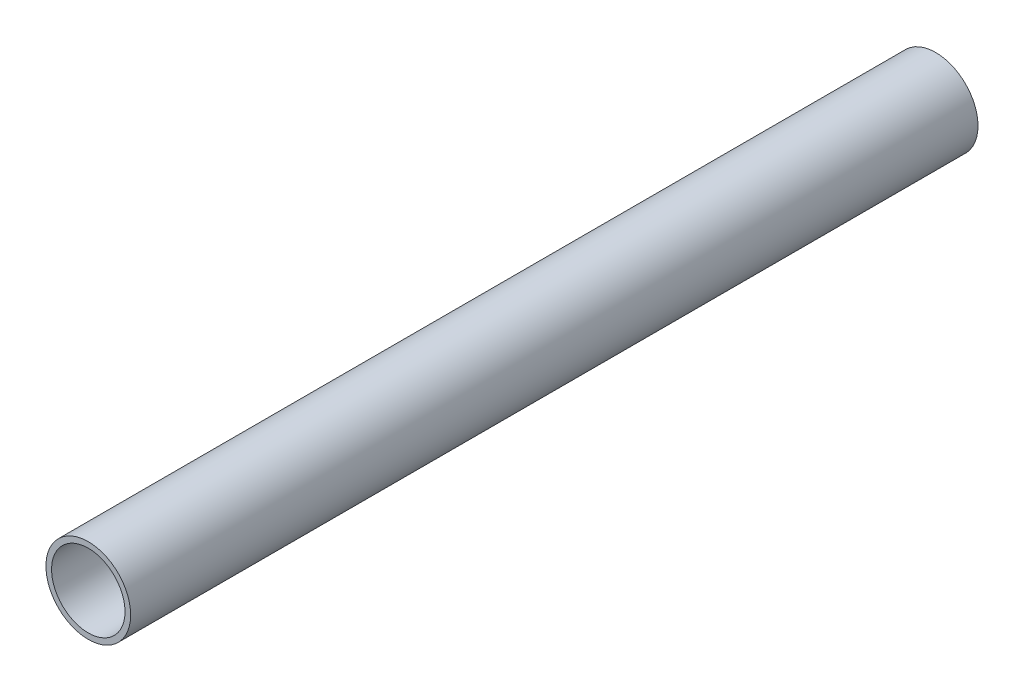
SolidWorks part; units mm, degrees
ref_plane "Front Plane" through (0, 0, 0) normal (0, 0, 1) x (1, 0, 0)
ref_plane "Top Plane" through (0, 0, 0) normal (0, 1, 0) x (1, 0, 0)
ref_plane "Right Plane" through (0, 0, 0) normal (1, 0, 0) x (0, 0, -1)
sketch "Sketch1" plane through (0, 0, 0) normal (0, 0, 1) x (1, 0, 0)
  circle A0 centre (-123, -48) radius 7.5
  circle A1 centre (-123, -48) radius 6.5
  dimension "D1" = 1
extrude "Boss-Extrude1" add sketch "Sketch1" along normal blind 150
